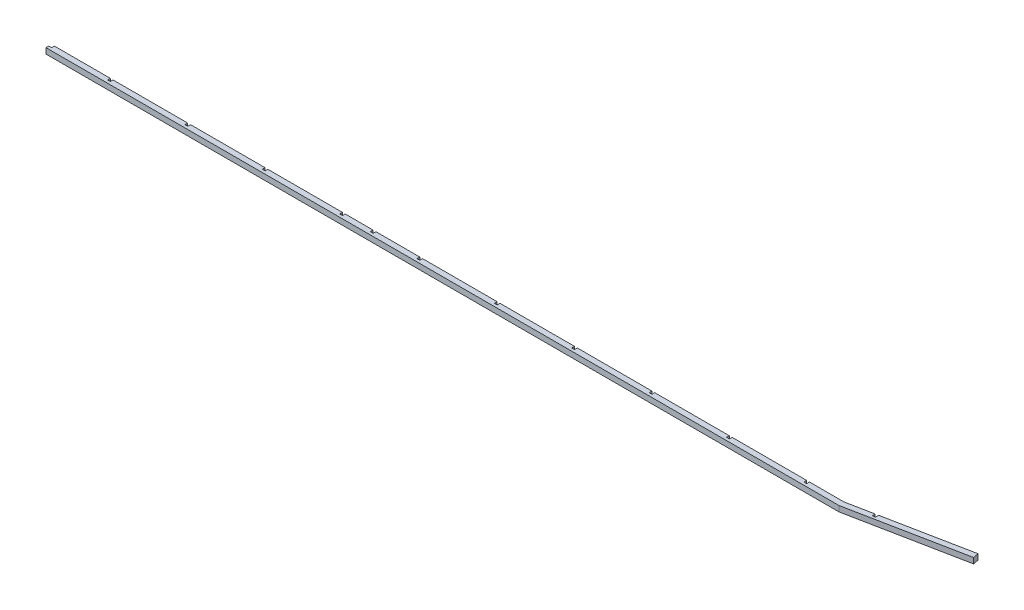
SolidWorks part; units mm, degrees
ref_plane "Front Plane" through (0, 0, 0) normal (0, 0, 1) x (1, 0, 0)
ref_plane "Top Plane" through (0, 0, 0) normal (0, 1, 0) x (1, 0, 0)
ref_plane "Right Plane" through (0, 0, 0) normal (1, 0, 0) x (0, 0, -1)
sketch "Sketch1" plane through (0, 0, 0) normal (0, 1, 0) x (1, 0, 0)
  line L0 (0, 0) -> (3, 0)
  line L1 (3, 0) -> (3, 3)
  line L2 (3, 3) -> (63, 3)
  line L3 (63, 3) -> (63, 0)
  line L4 (63, 0) -> (66, 0)
  line L5 (66, 0) -> (66, 3)
  line L6 (66, 3) -> (146, 3)
  line L7 (146, 3) -> (146, 0)
  line L8 (146, 0) -> (149, 0)
  line L9 (149, 0) -> (149, 3)
  line L10 (149, 3) -> (229, 3)
  line L11 (229, 3) -> (229, 0)
  line L12 (229, 0) -> (232, 0)
  line L13 (232, 0) -> (232, 3)
  line L14 (232, 3) -> (312, 3)
  line L15 (312, 3) -> (312, 0)
  line L16 (312, 0) -> (315, 0)
  line L17 (315, 0) -> (315, 3)
  line L18 (315, 3) -> (345, 3)
  line L19 (345, 3) -> (345, 0)
  line L20 (345, 0) -> (348, 0)
  line L21 (348, 0) -> (348, 3)
  line L22 (348, 3) -> (395, 3)
  line L23 (395, 3) -> (395, 0)
  line L24 (395, 0) -> (398, 0)
  line L25 (398, 0) -> (398, 3)
  line L26 (398, 3) -> (478, 3)
  line L27 (478, 3) -> (478, 0)
  line L28 (478, 0) -> (481, 0)
  line L29 (481, 0) -> (481, 3)
  line L30 (481, 3) -> (561, 3)
  line L31 (561, 3) -> (561, 0)
  line L32 (561, 0) -> (564, 0)
  line L33 (564, 0) -> (564, 3)
  line L34 (564, 3) -> (644, 3)
  line L35 (644, 3) -> (644, 0)
  line L36 (644, 0) -> (647, 0)
  line L37 (647, 0) -> (647, 3)
  line L38 (647, 3) -> (727, 3)
  line L39 (727, 3) -> (727, 0)
  line L40 (727, 0) -> (730, 0)
  line L41 (730, 0) -> (730, 3)
  line L42 (730, 3) -> (810, 3)
  line L43 (810, 3) -> (810, 0)
  line L44 (810, 0) -> (813, 0)
  line L45 (813, 0) -> (813, 3)
  line L46 (813, 3) -> (850, 3)
  line L47 (850, 3) -> (878, 8.5464)
  line L48 (878, 8.5464) -> (878, 5.5464)
  line L49 (878, 5.5464) -> (881, 5.5464)
  line L50 (881, 5.5464) -> (881, 9.1407)
  line L51 (881, 9.1407) -> (970, 26.7703)
  line L52 (878, 8.5464) -> (881, 9.1407) construction
  line L53 (970, 26.7703) -> (971.1659, 20.8847)
  line L54 (971.1659, 20.8847) -> (850.5885, -3)
  line L55 (850.5885, -3) -> (0, -3)
  line L56 (0, -3) -> (0, 0)
  point P53 (813, 1.5)
  dimension "D1" = 3
  dimension "D2" = 3
  dimension "D3" = 60
  dimension "D4" = 3
  dimension "D5" = 3
  dimension "D6" = 80
  dimension "D7" = 3
  dimension "D8" = 80
  dimension "D9" = 3
  dimension "D10" = 3
  dimension "D11" = 80
  dimension "D12" = 3
  dimension "D13" = 3
  dimension "D14" = 30
  dimension "D15" = 80
  dimension "D16" = 3
  dimension "D17" = 3
  dimension "D18" = 3
  dimension "D19" = 3
  dimension "D20" = 3
  dimension "D21" = 3
  dimension "D22" = 80
  dimension "D23" = 3
  dimension "D24" = 3
  dimension "D25" = 3
  dimension "D26" = 80
  dimension "D27" = 3
  dimension "D28" = 3
  dimension "D29" = 3
  dimension "D30" = 80
  dimension "D31" = 3
  dimension "D32" = 3
  dimension "D33" = 3
  dimension "D34" = 80
  dimension "D35" = 3
  dimension "D36" = 3
  dimension "D37" = 80
  dimension "D38" = 3
  dimension "D39" = 3
  dimension "D40" = 37
  dimension "D41" = 65
  dimension "D42" = 3
  dimension "D43" = 3
  dimension "D44" = 120
  dimension "D45" = 3
  dimension "D46" = 6
  dimension "D47" = 3
extrude "Boss-Extrude1" add sketch "Sketch1" along normal blind 6
